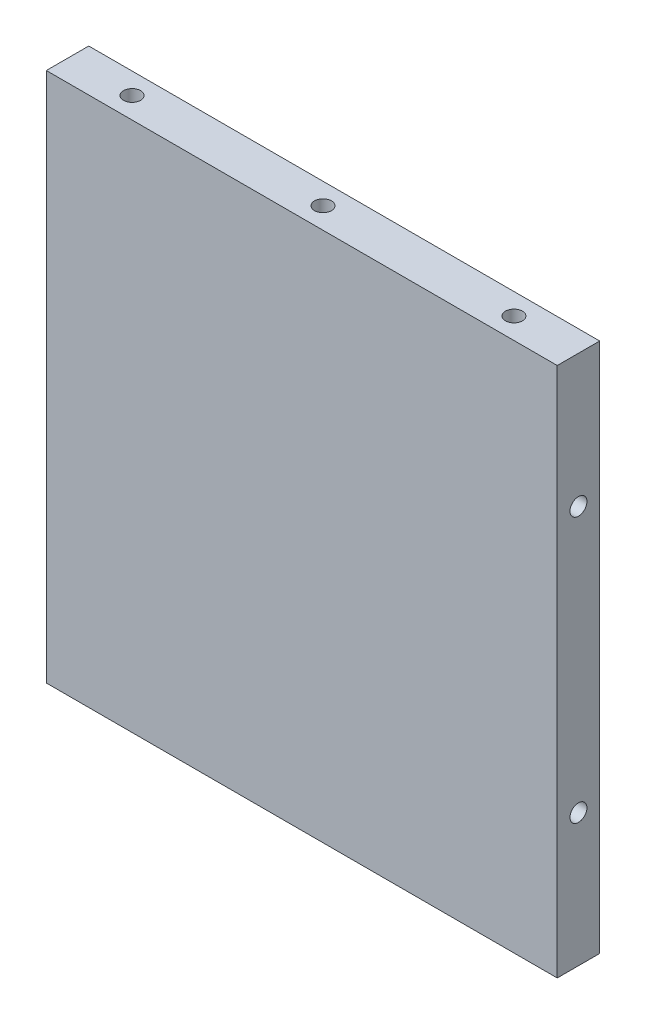
SolidWorks part; units mm, degrees
material "Oak"
ref_plane "Front Plane" through (0, 0, 0) normal (0, 0, 1) x (1, 0, 0)
ref_plane "Top Plane" through (0, 0, 0) normal (0, 1, 0) x (1, 0, 0)
ref_plane "Right Plane" through (0, 0, 0) normal (1, 0, 0) x (0, 0, -1)
sketch "Sketch1" plane through (0, 0, 0) normal (0, 1, 0) x (1, 0, 0)
  line L1 (0, 0) -> (120.4, 0)
  line L2 (0, 0) -> (0, 10)
  line L3 (0, 10) -> (120.4, 10)
  line L4 (120.4, 0) -> (120.4, 10)
  dimension "D1" = 10
  dimension "D2" = 120.4
extrude "Dodanie-wyciągnięcie1" add sketch "Sketch1" along normal blind 125
sketch "Szkic1" plane through (0, 125, 0) normal (0, 1, 0) x (1, 0, 0)
  line L0 (0, 5) -> (15.2, 5) construction
  line L1 (0, 10) -> (0, 0) construction
  line L2 (15.2, 5) -> (60.2, 5) construction
  line L3 (60.2, 5) -> (105.2, 5) construction
  circle A0 centre (15.2, 5) radius 2
  circle A1 centre (60.2, 5) radius 2
  circle A2 centre (105.2, 5) radius 2
extrude "Wytnij-wyciągnięcie1" cut sketch "Szkic1" against normal blind 10
sketch "Szkic2" plane through (0, 0, 0) normal (0, -1, 0) x (1, 0, 0)
  line L0 (0, -5) -> (15.2, -5) construction
  line L1 (0, -10) -> (0, 0) construction
  line L2 (15.2, -5) -> (60.2, -5) construction
  line L3 (60.2, -5) -> (105.2, -5) construction
  circle A0 centre (15.2, -5) radius 2
  circle A1 centre (60.2, -5) radius 2
  circle A2 centre (105.2, -5) radius 2
extrude "Wytnij-wyciągnięcie2" cut sketch "Szkic2" against normal blind 10
sketch "Szkic3" plane through (0, 0, 0) normal (-1, 0, 0) x (0, 0, 1)
  line L0 (-10, 62.5) -> (0, 62.5) construction
  line L1 (-10, 125) -> (-10, 0) construction
  line L2 (0, 125) -> (0, 0) construction
  line L3 (-5, 125) -> (-5, 62.5) construction
  line L4 (-10, 125) -> (0, 125) construction
  line L5 (-5, 62.5) -> (-5, 0) construction
  line L6 (-10, 0) -> (0, 0) construction
  circle A0 centre (-5, 93.75) radius 2
  circle A1 centre (-5, 31.25) radius 2
extrude "Wytnij-wyciągnięcie3" cut sketch "Szkic3" against normal blind 10
sketch "Szkic4" plane through (120.4, 0, 0) normal (1, 0, 0) x (0, 0, -1)
  line L0 (10, 62.5) -> (0, 62.5) construction
  line L1 (10, 125) -> (10, 0) construction
  line L2 (0, 125) -> (0, 0) construction
  line L3 (5, 125) -> (5, 62.5) construction
  line L4 (0, 125) -> (10, 125) construction
  line L5 (5, 62.5) -> (5, 0) construction
  line L6 (0, 0) -> (10, 0) construction
  circle A0 centre (5, 93.75) radius 2
  circle A1 centre (5, 31.25) radius 2
extrude "Wytnij-wyciągnięcie4" cut sketch "Szkic4" against normal blind 10
